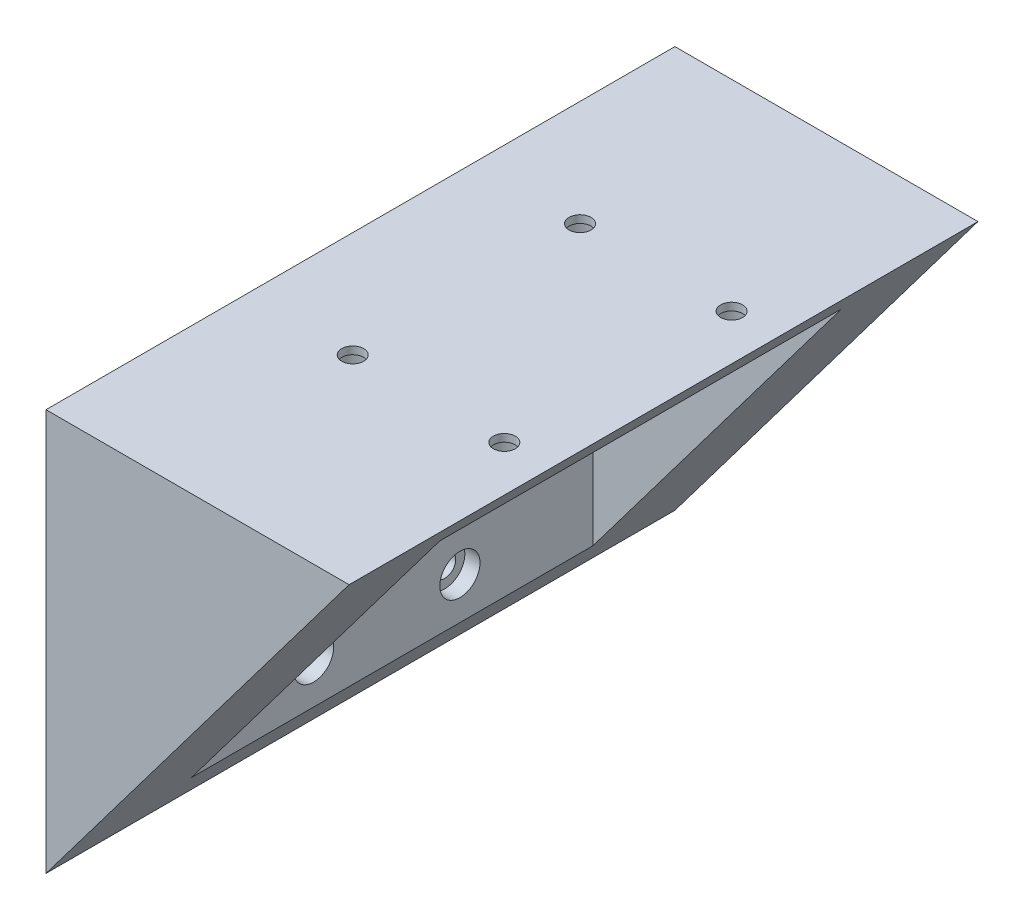
SolidWorks part; units mm, degrees
ref_plane "前视基准面" through (0, 0, 0) normal (0, 0, 1) x (1, 0, 0)
ref_plane "上视基准面" through (0, 0, 0) normal (0, 1, 0) x (1, 0, 0)
ref_plane "右视基准面" through (0, 0, 0) normal (1, 0, 0) x (0, 0, -1)
sketch "草图1" plane through (0, 0, 0) normal (0, 0, 1) x (1, 0, 0)
  line L0 (0, 2.3331) -> (0, -50.6669)
  line L1 (0, 2.3331) -> (40, 2.3331)
  line L2 (40, 2.3331) -> (0, -50.6669)
  dimension "D1" = 53
  dimension "D2" = 40
extrude "凸台-拉伸1" add sketch "草图1" along normal blind 83
ref_plane "基准面1" through (0, 0, 41.5) normal (0, 0, 1) x (1, 0, 0)
sketch "草图3" plane through (0, 0, 41.5) normal (0, 0, 1) x (1, 0, 0)
  line L0 (36.9811, -1.6669) -> (4.1736, -1.6669)
  line L1 (0, -50.6669) -> (40, 2.3331) construction
  line L2 (4.1736, -1.6669) -> (4.1736, -45.1369)
  line L3 (4.1736, -45.1369) -> (36.9811, -1.6669)
  line L5 (40, 2.3331) -> (0, 2.3331) construction
  line L11 (0, 2.3331) -> (0, -50.6669) construction
  dimension "D1" = 47.47
  dimension "D2" = 4
extrude "切除-拉伸1" cut sketch "草图3" against normal mid plane 53
sketch "草图4" plane through (4.1736, 0, 0) normal (1, 0, 0) x (0, 0, -1)
  line L0 (-42.235, -23.1869) -> (-42.24, -45.1369) construction
  line L1 (-61.49, -45.1369) -> (-22.99, -45.1369) construction
  line L2 (-61.49, -45.1369) -> (-61.49, -23.1869) construction
  line L3 (-61.49, -23.1869) -> (-22.99, -23.1869) construction
  line L4 (-22.99, -45.1369) -> (-22.99, -23.1869) construction
  line L7 (-15, -45.1369) -> (-68, -45.1369) construction
  line L8 (-51.86, -23.1869) -> (-51.86, -45.1369) construction
  line L9 (-61.49, -28.6869) -> (-22.99, -28.6869) construction
  line L10 (-61.49, -35.7919) -> (-22.99, -35.7919) construction
  line L11 (-61.485, -23.1869) -> (-42.235, -23.1869) construction
  line L12 (-51.86, -39.6369) -> (-32.5486, -39.6369) construction
  line L13 (-32.5486, -28.6869) -> (-32.5486, -39.6369) construction
  line L14 (-51.86, -28.6869) -> (-32.5486, -28.6869) construction
  line L15 (0, -50.6669) -> (0, 2.3331) construction
  circle A2 centre (-32.5486, -39.6369) radius 1.45
  circle A3 centre (-32.5486, -28.6869) radius 1.45
  circle A4 centre (-51.86, -28.6869) radius 1.45
  circle A5 centre (-51.86, -39.6369) radius 1.45
  point P0 (-41.5, -35.7919)
  dimension "D5" = 5.5
  dimension "D8" = 2.9
  dimension "D9" = 2.9
  dimension "D10" = 2.9
  dimension "D11" = 2.9
  dimension "D1" = 38.5
  dimension "D2" = 21.95
  dimension "D3" = 9.63
  dimension "D4" = 5.5
  dimension "D6" = 19.25
  dimension "D7" = 22.99
extrude "切除-拉伸3" cut sketch "草图4" against normal blind 10
sketch "草图5" plane through (0, -1.6669, 0) normal (0, -1, 0) x (1, 0, 0)
  line L0 (22, 41.5) -> (-22, 41.5) construction
  line L1 (13.9811, 26.5) -> (33.9811, 26.5) construction
  line L2 (13.9811, 26.5) -> (13.9811, 56.5) construction
  line L3 (13.9811, 56.5) -> (33.9811, 56.5) construction
  line L4 (33.9811, 26.5) -> (33.9811, 56.5) construction
  line L5 (13.9811, 26.5) -> (33.9811, 56.5) construction
  line L6 (13.9811, 56.5) -> (33.9811, 26.5) construction
  line L8 (36.9811, 15) -> (36.9811, 68) construction
  circle A2 centre (13.9811, 56.5) radius 1.45
  circle A3 centre (33.9811, 56.5) radius 1.45
  circle A4 centre (13.9811, 26.5) radius 1.45
  circle A5 centre (33.9811, 26.5) radius 1.45
  point P0 (23.9811, 41.5)
  dimension "D1" = 20
  dimension "D4" = 2.9
  dimension "D5" = 2.9
  dimension "D6" = 2.9
  dimension "D7" = 2.9
  dimension "D2" = 30
  dimension "D3" = 3
extrude "切除-拉伸4" cut sketch "草图5" against normal blind 10
sketch "草图6" plane through (0, -1.6669, 0) normal (0, -1, 0) x (1, 0, 0)
  circle A0 centre (13.9811, 56.5) radius 2.8
  circle A1 centre (33.9811, 56.5) radius 2.8
  circle A2 centre (13.9811, 26.5) radius 2.8
  circle A3 centre (33.9811, 26.5) radius 2.8
  dimension "D1" = 5.6
  dimension "D2" = 5.6
  dimension "D3" = 5.6
  dimension "D4" = 5.6
extrude "切除-拉伸5" cut sketch "草图6" against normal blind 3
sketch "草图7" plane through (4.1736, 0, 0) normal (1, 0, 0) x (0, 0, -1)
  circle A0 centre (-51.86, -28.6869) radius 2.65
  circle A1 centre (-32.5486, -28.6869) radius 2.65
  circle A2 centre (-51.86, -39.6369) radius 2.65
  circle A3 centre (-32.5486, -39.6369) radius 2.65
  dimension "D1" = 5.3
  dimension "D2" = 5.3
  dimension "D3" = 5.3
  dimension "D4" = 5.3
extrude "切除-拉伸6" cut sketch "草图7" against normal blind 2
